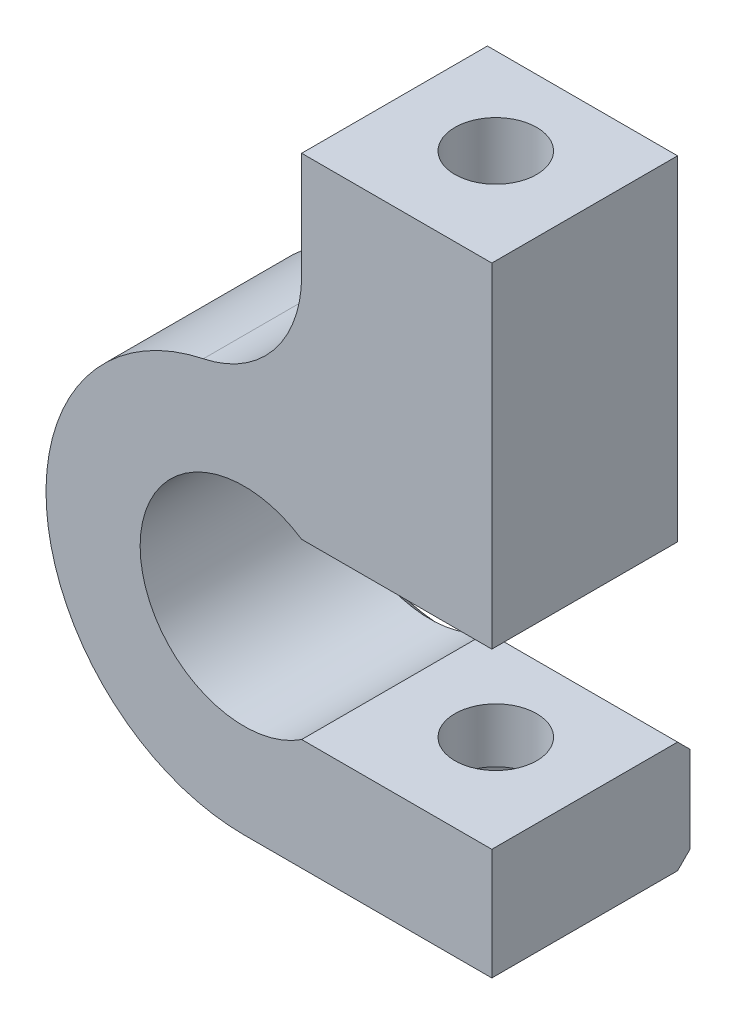
SolidWorks part; units mm, degrees
ref_plane "Front Plane" through (0, 0, 0) normal (0, 0, 1) x (1, 0, 0)
ref_plane "Top Plane" through (0, 0, 0) normal (0, 1, 0) x (1, 0, 0)
ref_plane "Right Plane" through (0, 0, 0) normal (1, 0, 0) x (0, 0, -1)
sketch "Sketch1" plane through (0, 0, 0) normal (0, 0, 1) x (1, 0, 0)
  line L0 (0, 8) -> (10, 8)
  line L1 (10, 8) -> (10, 3.5)
  line L2 (10, 3.5) -> (2.3216, 3.5)
  line L3 (-11.5353, 0) -> (18.1518, 0) construction
  line L4 (10, -3.5) -> (2.3216, -3.5)
  line L5 (10, -8) -> (10, -3.5)
  line L6 (0, -8) -> (10, -8)
  arc A0 (2.3216, 3.5) -> (2.3216, -3.5) centre (0, 0) ccw
  arc A2 (0, 8) -> (0, -8) centre (0, 0) ccw
  dimension "D1" = 4.2
  dimension "D2" = 8
  dimension "D3" = 10
  dimension "D4" = 7
extrude "Boss-Extrude1" add sketch "Sketch1" along normal blind 8
sketch "Sketch2" plane through (0, -8, 0) normal (0, -1, 0) x (1, 0, 0)
  line L1 (0, 8) -> (10, 8) construction
  line L3 (0, 8) -> (0, 0) construction
  circle A0 centre (6.16, 4) radius 1.65
  dimension "D1" = 4
  dimension "D2" = 3.3
  dimension "D3" = 6.16
extrude "Cut-Extrude1" cut sketch "Sketch2" against normal through all
sketch "Sketch3" plane through (0, -8, 0) normal (0, -1, 0) x (1, 0, 0)
  line L1 (7.76, 6.7713) -> (4.56, 6.7713)
  line L2 (4.56, 6.7713) -> (2.96, 4)
  line L3 (2.96, 4) -> (4.56, 1.2287)
  line L4 (4.56, 1.2287) -> (7.76, 1.2287)
  line L5 (7.76, 1.2287) -> (9.36, 4)
  line L6 (9.36, 4) -> (7.76, 6.7713)
  circle A0 centre (6.16, 4) radius 3.2 construction
  dimension "D1" = 6.4
extrude "Cut-Extrude2" cut sketch "Sketch3" against normal blind 2.3
sketch "Sketch4" plane through (0, 3.5, 0) normal (0, -1, 0) x (1, 0, 0)
  line L4 (2.3216, 0) -> (10, 0)
  line L5 (10, 0) -> (10, 8)
  line L6 (10, 8) -> (2.3216, 8)
  line L7 (2.3216, 8) -> (2.3216, 0)
  line L8 (2.3216, 0) -> (10, 0)
  line L9 (10, 0) -> (10, 8)
  line L10 (10, 8) -> (2.3216, 8)
  line L11 (2.3216, 8) -> (2.3216, 0)
  circle A1 centre (6.16, 4) radius 1.65
  circle A2 centre (6.16, 4) radius 1.65
  dimension "D1" = 0
  dimension "D2" = 0
extrude "Boss-Extrude2" add sketch "Sketch4" against normal blind 13.5
fillet "Fillet1" radius 5 1 edges at (2.3216, 8, 4)
chamfer "Chamfer1" distance 0.5 angle 45 9 edges at (5, -8, 0) (-7.957, -0.8286, 0) (1.2043, 9.5708, 0) (2.3216, 14.8605, 0) (6.1608, 17, 0) (10, 10.25, 0) (6.1608, 3.5, 0) (6.1608, -3.5, 0) (-4.2, 0, 0)
